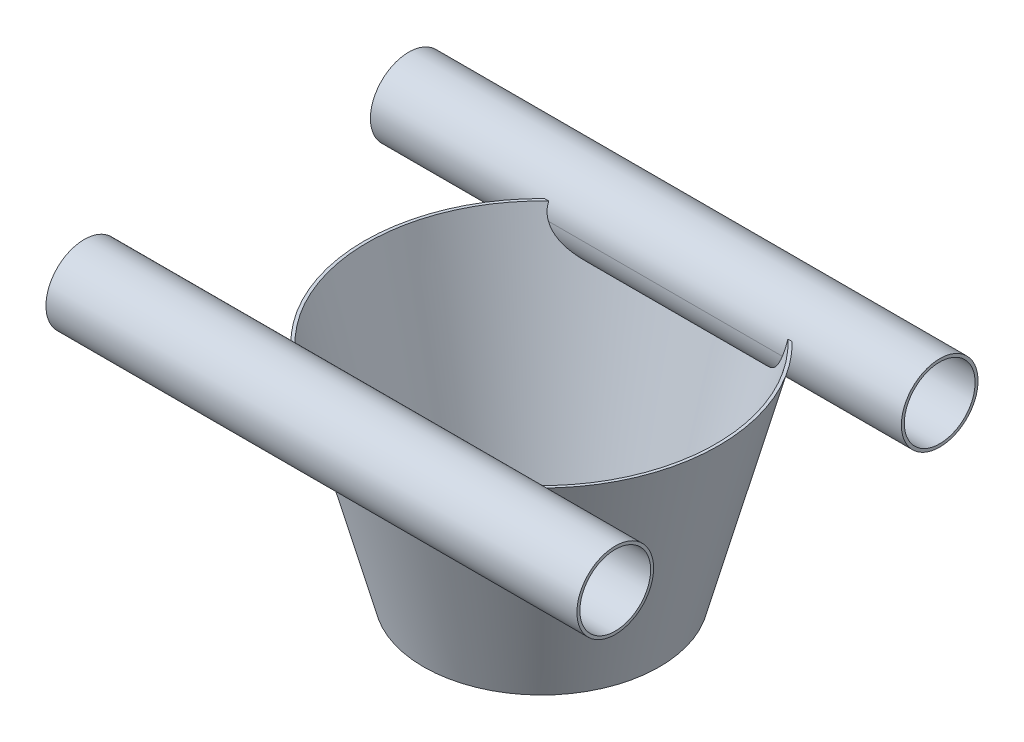
SolidWorks part; units mm, degrees
ref_plane "Front Plane" through (0, 0, 0) normal (0, 0, 1) x (1, 0, 0)
ref_plane "Top Plane" through (0, 0, 0) normal (0, 1, 0) x (1, 0, 0)
ref_plane "Right Plane" through (0, 0, 0) normal (1, 0, 0) x (0, 0, -1)
sketch "Sketch1" plane through (0, 0, 0) normal (0, 1, 0) x (1, 0, 0)
  circle A0 centre (0, 0) radius 40
  dimension "D1" = 80
extrude "Boss-Extrude1" add sketch "Sketch1" along normal blind 75 draft 15 contours A0 draft outward yes
sketch "Sketch2" plane through (0, 0, 0) normal (0, -1, 0) x (1, 0, 0)
  circle A0 centre (0, 0) radius 39
  dimension "D1" = 78
extrude "Cut-Extrude1" cut sketch "Sketch2" against normal through all draft 15 draft outward yes
sketch "Sketch6" plane through (0, 0, 0) normal (0, -1, 0) x (1, 0, 0)
  circle A0 centre (0, 0) radius 39
sketch "Sketch7" plane through (0, 0, 0) normal (1, 0, 0) x (0, 0, -1)
  line L0 (-39, 0) -> (39, 0) construction
  line L1 (59.0962, 75) -> (-59.0962, 75) construction
  line L2 (0, 75) -> (0, 0)
  circle A0 centre (-55, 70) radius 13
  circle A1 centre (55, 70) radius 13
  dimension "D1" = 26
  dimension "D2" = 70
  dimension "D3" = 55
extrude "Cut-Extrude3" cut sketch "Sketch7" against normal through all and the other way through all contours A0 | A1
sketch "Sketch9" plane through (0, 0, 0) normal (1, 0, 0) x (0, 0, -1)
  line L0 (0, 75) -> (0, 0) construction
  circle A0 centre (-55, 70) radius 13
  circle A1 centre (-55, 70) radius 12
  circle A2 centre (55, 70) radius 12
  circle A3 centre (55, 70) radius 13
  dimension "D1" = 26
  dimension "D2" = 24
extrude "Boss-Extrude2" add sketch "Sketch9" along normal blind 80 and the other way blind 100
